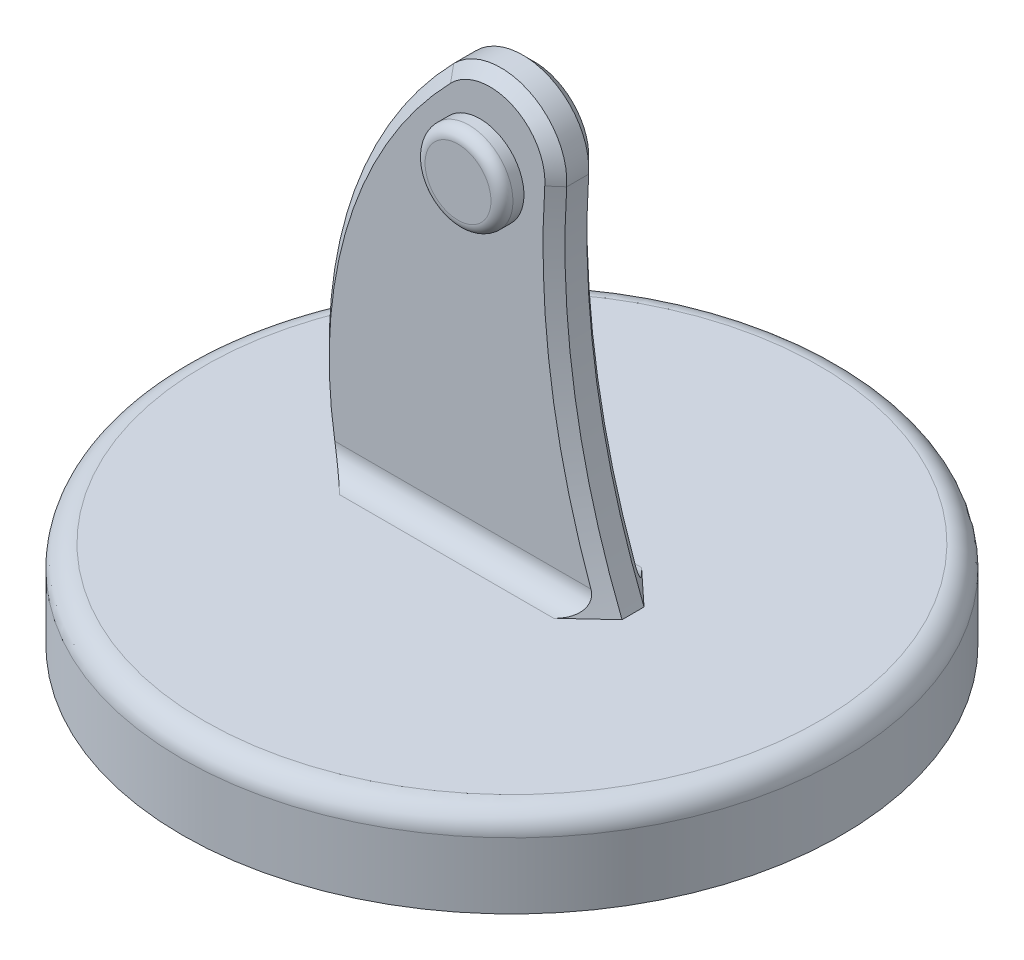
SolidWorks part; units mm, degrees
ref_plane "Front Plane" through (0, 0, 0) normal (0, 0, 1) x (1, 0, 0)
ref_plane "Top Plane" through (0, 0, 0) normal (0, 1, 0) x (1, 0, 0)
ref_plane "Right Plane" through (0, 0, 0) normal (1, 0, 0) x (0, 0, -1)
sketch "Sketch1" plane through (0, 0, 0) normal (0, 1, 0) x (1, 0, 0)
  circle A0 centre (0, 0) radius 75
  dimension "D1" = 150
extrude "Boss-Extrude1" add sketch "Sketch1" along normal blind 20
fillet "Fillet1" radius 5 1 edges at (0, 20, 75)
sketch "Sketch2" plane through (0, 0, 0) normal (0, 0, 1) x (1, 0, 0)
  line L0 (0, 0) -> (0, 100) construction
  line L1 (-35, 12.4445) -> (30, 12.4445)
  line L2 (30, 12.4445) -> (30, 14.2253)
  arc A0 (14.9673, 99.01) -> (-10.7504, 110.4609) centre (0, 100) ccw
  arc A1 (-35, 12.4445) -> (-10.7504, 110.4609) centre (60.9187, 40.7218) cw
  arc A2 (30, 14.2253) -> (14.9673, 99.01) centre (194.5748, 87.1302) cw
  dimension "D4" = 30
  dimension "D5" = 180
  dimension "D6" = 100
  dimension "D1" = 30
  dimension "D2" = 35
  dimension "D3" = 100
extrude "Boss-Extrude2" add sketch "Sketch2" along normal mid plane 10
chamfer "Chamfer2" distance 2.5 angle 45 3 edges at (16.8188, 58.7964, 5) (-35.145, 68.5025, 5) (6.1013, 113.7031, 5)
chamfer "Chamfer3" distance 2.5 angle 45 3 edges at (16.8188, 58.7964, -5) (-35.145, 68.5025, -5) (6.1013, 113.7031, -5)
fillet "Fillet2" radius 5 2 edges at (-4.742, 20, -5) (-4.742, 20, 5)
sketch "Sketch3" plane through (0, 0, 5) normal (0, 0, 1) x (1, 0, 0)
  line L0 (0, 0) -> (0, 131.1183) construction
  circle A0 centre (-2.2668, 95.0648) radius 10
  dimension "D1" = 20
extrude "Boss-Extrude4" add sketch "Sketch3" along normal blind 5
fillet "Fillet5" radius 2.5 1 edges at (7.7332, 95.0648, 10)
sketch "Sketch5" plane through (0, 0, -5) normal (0, 0, -1) x (-1, 0, 0)
  circle A0 centre (2.4601, 95.7611) radius 5
extrude "Cut-Extrude4" cut sketch "Sketch5" against normal blind 10 contours A0
